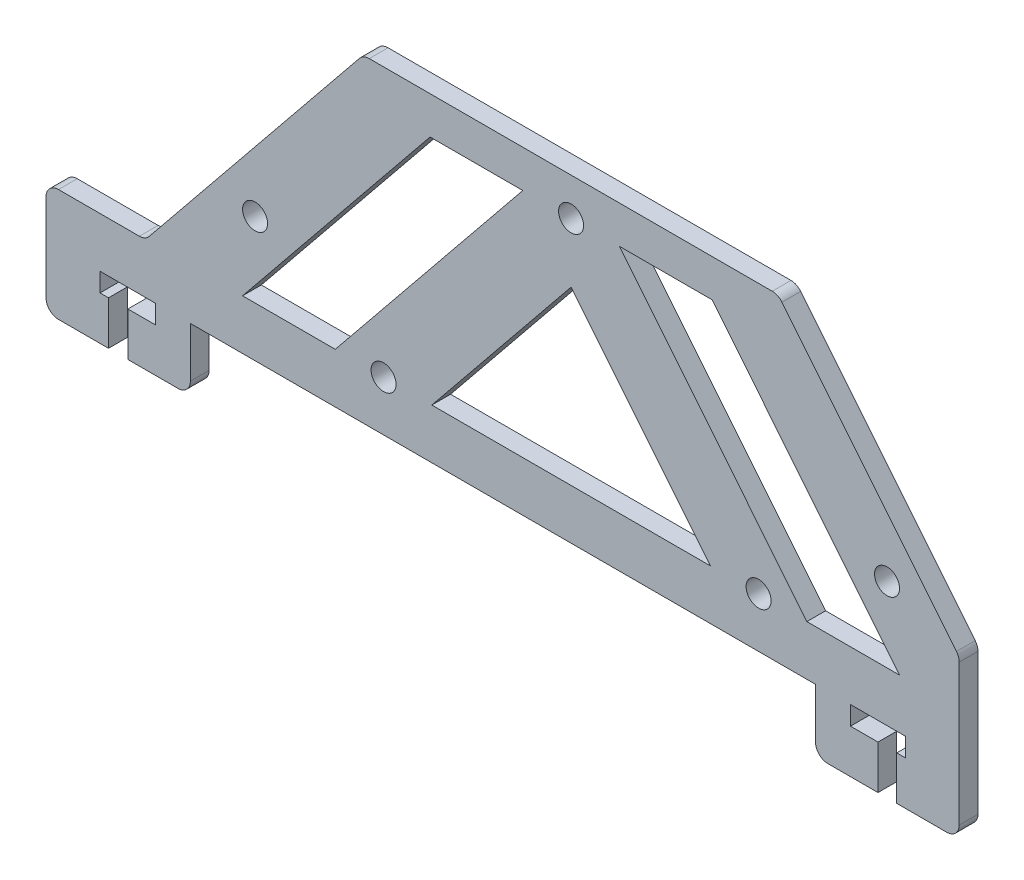
SolidWorks part; units mm, degrees
material "Zoltek Panex 33"
ref_plane "前视基准面" through (0, 0, 0) normal (0, 0, 1) x (1, 0, 0)
ref_plane "上视基准面" through (0, 0, 0) normal (0, 1, 0) x (1, 0, 0)
ref_plane "右视基准面" through (0, 0, 0) normal (1, 0, 0) x (0, 0, -1)
sketch "草图1" plane through (0, 0, 0) normal (0, 0, 1) x (1, 0, 0)
  line L0 (34.6798, 30.1003) -> (63.3, 30.1003) construction
  line L1 (64.3, -0.3997) -> (59.3, -0.3997)
  line L2 (64.3, -0.3997) -> (64.3, 12.2412)
  line L4 (-8.75, -0.3997) -> (-8.75, 8.6003)
  line L5 (57.8, -0.3997) -> (52.8, -0.3997)
  line L7 (52.8, -0.3997) -> (52.8, 4.6003)
  line L8 (52.8, 4.6003) -> (2.8, 4.6003)
  line L9 (2.8, -0.3997) -> (2.8, 4.6003)
  line L18 (2.8, -0.3997) -> (-2.2, -0.3997)
  line L19 (-3.75, -0.3997) -> (-8.75, -0.3997)
  line L20 (57.8, -0.3997) -> (57.8, 3.1003)
  line L25 (59.3, -0.3997) -> (59.3, 3.1003)
  line L30 (57.8, 3.1003) -> (55.6, 3.1003)
  line L31 (55.6, 3.1003) -> (55.6, 4.6003)
  line L32 (55.6, 4.6003) -> (55.6, 3.1003) construction
  line L33 (55.6, 4.6003) -> (60, 4.6003)
  line L34 (60, 4.6003) -> (60, 3.1003)
  line L35 (60, 3.1003) -> (59.3, 3.1003)
  line L36 (-3.75, -0.3997) -> (-3.75, 3.1003)
  line L42 (-2.2, 3.1003) -> (-2.2, -0.3997)
  line L43 (-3.75, 3.1003) -> (-4.4252, 3.1003)
  line L44 (-4.4252, 3.1003) -> (-4.4252, 4.6003)
  line L45 (-4.4252, 4.6003) -> (0, 4.6003)
  line L46 (0, 4.6003) -> (0, 3.1003)
  line L47 (0, 3.1003) -> (-2.2, 3.1003)
  line L48 (59.5276, 8.6003) -> (52.1122, 8.6003)
  line L49 (52.1122, 8.6003) -> (37.1122, 27.1003)
  line L50 (34.8451, 30.1003) -> (16.6288, 30.1003)
  line L51 (16.6288, 30.1003) -> (-0.8036, 8.6003)
  line L52 (-0.8036, 8.6003) -> (-8.75, 8.6003)
  line L53 (-8.75, 40.3264) -> (-8.75, 78.6003) construction
  line L54 (33.25, 22.3369) -> (33.25, 27.1003) construction
  line L55 (18.25, 8.6003) -> (33.25, 27.1003) construction
  line L56 (33.25, 27.1003) -> (48.25, 8.6003) construction
  line L57 (18.25, 8.6003) -> (48.25, 8.6003) construction
  line L58 (44.3878, 8.6003) -> (33.25, 22.3369)
  line L59 (33.25, 22.3369) -> (22.1122, 8.6003)
  line L60 (22.1122, 8.6003) -> (44.3878, 8.6003)
  line L61 (64.3, 12.2412) -> (49.8197, 30.1003)
  line L62 (49.8197, 30.1003) -> (34.8451, 30.1003)
  line L63 (59.5276, 8.6003) -> (44.5276, 27.1003)
  line L64 (44.5276, 27.1003) -> (37.1122, 27.1003)
  line L65 (21.9724, 27.1003) -> (29.3878, 27.1003)
  line L66 (14.3878, 8.6003) -> (29.3878, 27.1003)
  line L67 (6.9724, 8.6003) -> (21.9724, 27.1003)
  line L68 (6.9724, 8.6003) -> (14.3878, 8.6003)
  circle A0 centre (33.25, 27.1003) radius 1
  circle A1 centre (48.25, 8.6003) radius 1
  circle A2 centre (18.25, 8.6003) radius 1
  circle A3 centre (18.25, 8.6003) radius 1 construction
  circle A4 centre (48.25, 8.6003) radius 1 construction
  circle A5 centre (33.25, 27.1003) radius 1 construction
  circle A6 centre (58.525, 14.6003) radius 1
  circle A7 centre (58.525, 14.6003) radius 1 construction
  circle A8 centre (7.975, 14.6003) radius 1
  dimension "D1" = 14.8
  dimension "D2" = 3
  dimension "D3" = 3
  dimension "D4" = 3
  dimension "D5" = 3
  dimension "D6" = 3
  dimension "D8" = 5
  dimension "D9" = 50
extrude "凸台-拉伸1" add sketch "草图1" along normal blind 1.5
fillet "圆角1" radius 1 9 edges at (2.8, -0.3997, 0.75) (52.8, -0.3997, 0.75) (64.3, -0.3997, 0.75) (64.3, 12.2412, 0.75) (49.8197, 30.1003, 0.75) (16.6288, 30.1003, 0.75) (-0.8036, 8.6003, 0.75) (-8.75, 8.6003, 0.75) (-8.75, -0.3997, 0.75)
